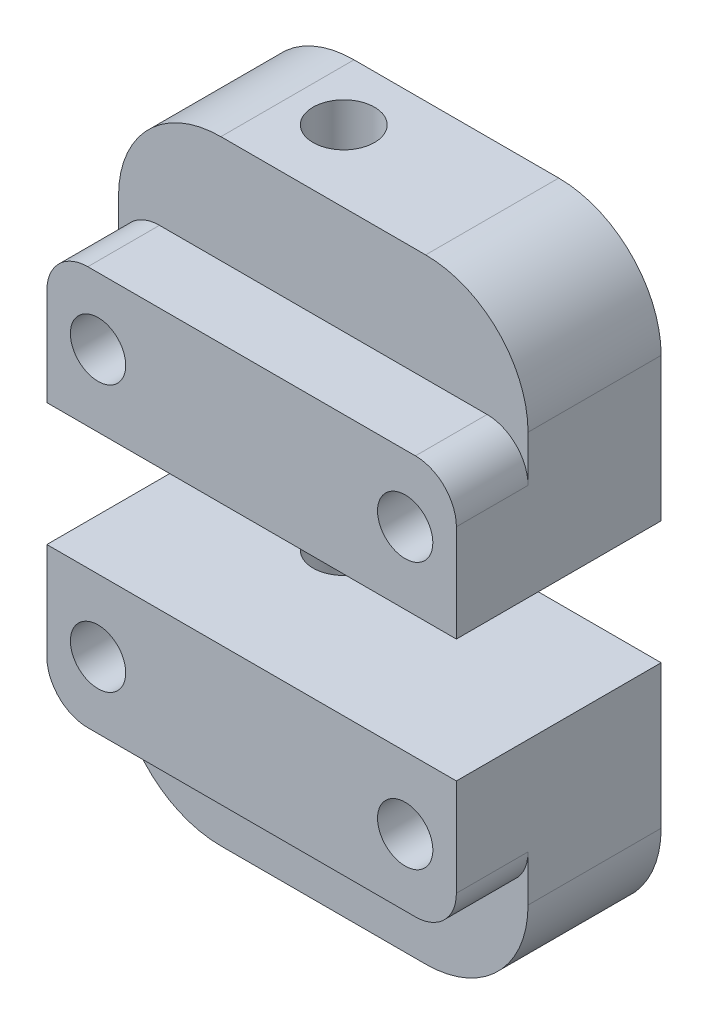
SolidWorks part; units mm, degrees
material "PLA"
ref_plane "前视基准面" through (0, 0, 0) normal (0, 0, 1) x (1, 0, 0)
ref_plane "上视基准面" through (0, 0, 0) normal (0, 1, 0) x (1, 0, 0)
ref_plane "右视基准面" through (0, 0, 0) normal (1, 0, 0) x (0, 0, -1)
sketch "草图1" plane through (0, 0, 0) normal (0, 1, 0) x (1, 0, 0)
  line L0 (0, 10) -> (0, 0) construction
  line L1 (-10, 0) -> (10, 0)
  line L5 (10, 10) -> (-10, 10)
  line L6 (10, 0) -> (-10, 0)
  line L7 (10, 0) -> (10, 10)
  line L9 (-10, 0) -> (-10, 10)
  line L11 (10, 5) -> (-10, 5) construction
  circle A1 centre (-2.5, 7) radius 1.5
  point P6 (0, 0)
  dimension "D5" = 12.5
  dimension "D2" = 3
  dimension "D1" = 10
  dimension "D3" = 20
  dimension "D4" = 7
extrude "凸台-拉伸1" add sketch "草图1" along normal mid plane 30
sketch "草图2" plane through (0, 0, 0) normal (1, 0, 0) x (0, 0, -1)
  line L2 (0, -9.75) -> (0, 9.75)
  line L7 (0, 15) -> (0, -15) construction
  line L8 (0, -15) -> (10, -15) construction
  line L9 (0, 15) -> (3.5, 15)
  line L10 (0, 15) -> (0, 9.75)
  line L11 (0, 9.75) -> (3.5, 9.75)
  line L12 (3.5, 15) -> (3.5, 9.75)
  line L13 (1.75, 9.75) -> (1.75, 15) construction
  line L14 (0, 12.375) -> (3.5, 12.375) construction
  line L15 (0, -9.75) -> (3.5, -9.75)
  line L16 (0, -9.75) -> (0, -15)
  line L17 (0, -15) -> (3.5, -15)
  line L18 (3.5, -9.75) -> (3.5, -15)
  line L19 (1.75, -15) -> (1.75, -9.75) construction
  line L20 (0, -12.375) -> (3.5, -12.375) construction
  point P189 (1.75, 12.375)
  point P214 (1.75, -12.375)
  dimension "D1" = 3.5
  dimension "D2" = 19.5
extrude "切除-拉伸3" cut sketch "草图2" against normal through all both and the other way through all contours L18 L15 L16 L17 | L12 L9 L10 L11
sketch "草图4" plane through (0, 0, -10) normal (0, 0, -1) x (-1, 0, 0)
  line L0 (0, 15) -> (0, -15) construction
  line L1 (-10, -15) -> (10, -15) construction
  line L2 (-7.5, -6.5) -> (7.5, -6.5) construction
  line L3 (-10, 0) -> (10, 0) construction
  line L4 (-10, 15) -> (-10, -15) construction
  line L5 (10, 15) -> (10, -15) construction
  circle A0 centre (-7.5, -6.5) radius 1.35
  circle A1 centre (7.5, -6.5) radius 1.35
  circle A2 centre (7.5, 6.5) radius 1.35
  circle A3 centre (-7.5, 6.5) radius 1.35
  point P8 (0, 0)
  dimension "D2" = 2.7
  dimension "D1" = 15
  dimension "D3" = 13
extrude "切除-拉伸4" cut sketch "草图4" against normal through all
fillet "圆角1" radius 5 4 edges at (-10, 15, -6.75) (-10, -15, -6.75) (10, -15, -6.75) (10, 15, -6.75)
fillet "圆角2" radius 2 4 edges at (-10, -9.75, -1.75) (-10, 9.75, -1.75) (10, 9.75, -1.75) (10, -9.75, -1.75)
sketch "草图6" plane through (0, 0, -10) normal (0, 0, -1) x (-1, 0, 0)
  line L1 (-5, -15) -> (5, -15) construction
  line L10 (10, 0) -> (0, 0) construction
  line L12 (10, 10) -> (10, -10) construction
  line L13 (0, 0) -> (0, -15) construction
  circle A10 centre (-7.5, 6.5) radius 2.25
  circle A11 centre (-7.5, 6.5) radius 1.35 construction
  circle A12 centre (-7.5, -6.5) radius 2.25
  circle A13 centre (7.5, -6.5) radius 2.25
  circle A14 centre (7.5, 6.5) radius 2.25
  dimension "D1" = 4.5
extrude "切除-拉伸6" cut sketch "草图6" against normal blind 3
sketch "草图7" plane through (-10, 0, 0) normal (-1, 0, 0) x (0, 0, 1)
  line L0 (0, 7.75) -> (0, -7.75) construction
  line L1 (0, -3) -> (-10, -3)
  line L2 (0, -3) -> (0, 3)
  line L3 (0, 3) -> (-10, 3)
  line L4 (-10, -3) -> (-10, 3)
  line L5 (-5, 3) -> (-5, -3) construction
  line L6 (0, 0) -> (-10, 0) construction
  line L7 (-10, 10) -> (-10, -10) construction
  point P144 (-5, 0)
  dimension "D1" = 6
extrude "切除-拉伸7" cut sketch "草图7" against normal through all
move or copy body "实体-移动/复制1" [suppressed] bodies to move or copy 113 115
